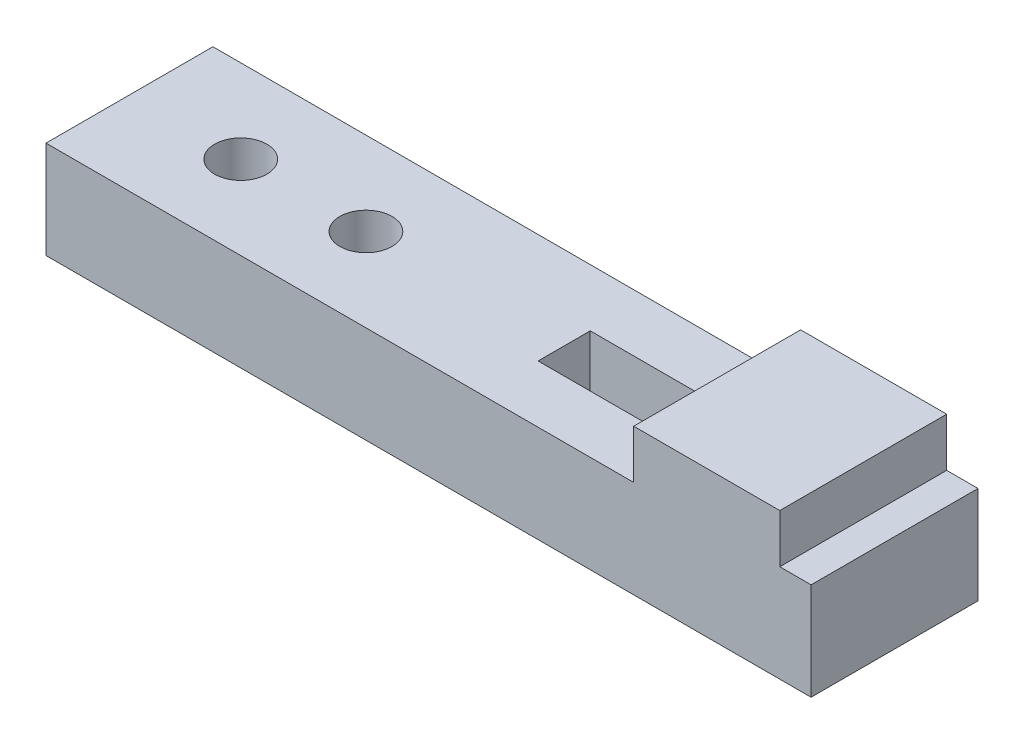
SolidWorks part; units mm, degrees
ref_plane "前视基准面" through (0, 0, 0) normal (0, 0, 1) x (1, 0, 0)
ref_plane "上视基准面" through (0, 0, 0) normal (0, 1, 0) x (1, 0, 0)
ref_plane "右视基准面" through (0, 0, 0) normal (1, 0, 0) x (0, 0, -1)
other "Configuration Table"
sketch "01_Base_Profile" plane through (0, 0, 0) normal (0, 1, 0) x (1, 0, 0)
  line L1 (-110, -24) -> (110, -24)
  line L2 (-110, -24) -> (-110, 24)
  line L3 (-110, 24) -> (110, 24)
  line L4 (110, -24) -> (110, 24)
  line L5 (-110, -24) -> (110, 24) construction
  line L6 (-110, 24) -> (110, -24) construction
  line L7 (15, -7.5) -> (75, -7.5)
  line L8 (15, -7.5) -> (15, 7.5)
  line L9 (15, 7.5) -> (75, 7.5)
  line L10 (75, -7.5) -> (75, 7.5)
  line L11 (15, -7.5) -> (75, 7.5) construction
  line L12 (15, 7.5) -> (75, -7.5) construction
  circle A0 centre (-78, 0) radius 7.5
  circle A1 centre (-42, 0) radius 7.5
  point P0 (0, 0)
  point P10 (45, 0)
extrude "01_Base_Extrude" add sketch "01_Base_Profile" along normal blind 28
sketch "02_Boss_Profile" plane through (0, 0, 0) normal (0, 1, 0) x (1, 0, 0)
  line L0 (110, 24) -> (-110, 24) construction
  line L1 (59, -24) -> (101, -24)
  line L2 (59, -24) -> (59, 24)
  line L3 (59, 24) -> (101, 24)
  line L4 (101, -24) -> (101, 24)
  line L5 (59, -24) -> (101, 24) construction
  line L6 (59, 24) -> (101, -24) construction
  point P0 (80, 0)
extrude "02_Reinforcement_Boss" add sketch "02_Boss_Profile" along normal blind 42
